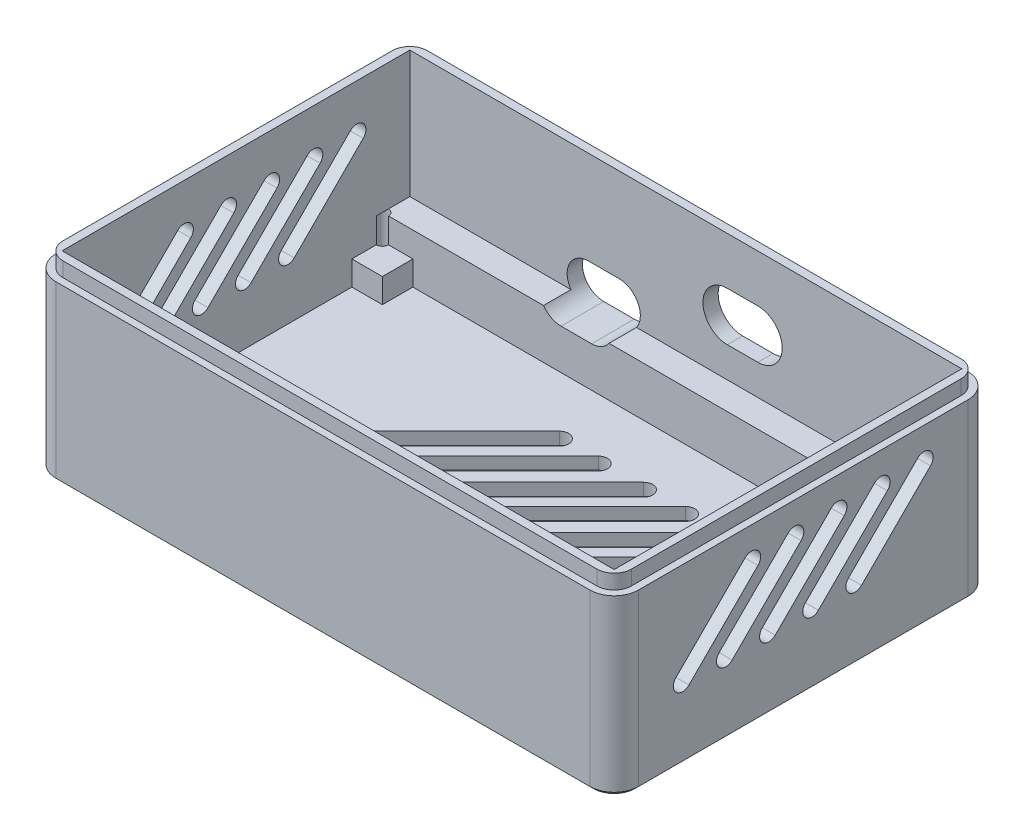
SolidWorks part; units mm, degrees
ref_plane "Front Plane" through (0, 0, 0) normal (0, 0, 1) x (1, 0, 0)
ref_plane "Top Plane" through (0, 0, 0) normal (0, 1, 0) x (1, 0, 0)
ref_plane "Right Plane" through (0, 0, 0) normal (1, 0, 0) x (0, 0, -1)
sketch "Croquis_contorno" plane through (0, 0, 0) normal (0, 1, 0) x (1, 0, 0)
  line L0 (-43.75, -28.75) -> (43.75, -28.75)
  line L1 (47.75, -24.75) -> (47.75, 29.25)
  line L2 (43.75, 33.25) -> (-43.75, 33.25)
  line L3 (-47.75, 29.25) -> (-47.75, -24.75)
  arc A0 (43.75, -28.75) -> (47.75, -24.75) centre (43.75, -24.75) ccw
  arc A1 (47.75, 29.25) -> (43.75, 33.25) centre (43.75, 29.25) ccw
  arc A2 (-43.75, 33.25) -> (-47.75, 29.25) centre (-43.75, 29.25) ccw
  arc A3 (-47.75, -24.75) -> (-43.75, -28.75) centre (-43.75, -24.75) ccw
  dimension "D3" = 4
  dimension "D1" = 95.5
  dimension "D2" = 62
extrude "Cuerpo" add sketch "Croquis_contorno" along normal blind 28.5
ref_plane "Plano_Top Plane_+28_5" through (0, 28.5, 0) normal (0, 1, 0) x (1, 0, 0)
sketch "Croquis_hueco_ESP32" plane through (0, 28.5, 0) normal (0, 1, 0) x (1, 0, 0)
  line L1 (-45.25, -26.25) -> (45.25, -26.25)
  line L2 (-45.25, -26.25) -> (-45.25, 30.75)
  line L3 (-45.25, 30.75) -> (45.25, 30.75)
  line L4 (45.25, -26.25) -> (45.25, 30.75)
  line L5 (-45.25, -26.25) -> (45.25, 30.75) construction
  line L6 (-45.25, 30.75) -> (45.25, -26.25) construction
  dimension "D1" = 90.5
  dimension "D2" = 57
extrude "Hueco_ESP32" cut sketch "Croquis_hueco_ESP32" against normal blind 18.4
ref_plane "Plano_Top Plane_+10_1" through (0, 10.1, 0) normal (0, 1, 0) x (1, 0, 0)
sketch "Croquis_hueco_PCB" plane through (0, 10.1, 0) normal (0, 1, 0) x (1, 0, 0)
  line L0 (45.25, -26.25) -> (45.25, 30.75) construction
  line L1 (-45.25, -26.25) -> (45.25, -26.25)
  line L2 (-45.25, -26.25) -> (-45.25, 26.25)
  line L3 (-45.25, 26.25) -> (45.25, 26.25)
  line L4 (45.25, -26.25) -> (45.25, 26.25)
  line L5 (-45.25, -26.25) -> (45.25, 26.25) construction
  line L6 (-45.25, 26.25) -> (45.25, -26.25) construction
  point P0 (0, 0)
  dimension "D1" = 90.5
  dimension "D2" = 52.5
extrude "Hueco_PCB" cut sketch "Croquis_hueco_PCB" against normal blind 8.1
sketch "Croquis_labio" plane through (0, 28.5, 0) normal (0, 1, 0) x (1, 0, 0)
  line L0 (-43.75, -27.6) -> (43.75, -27.6)
  line L1 (46.6, -24.75) -> (46.6, 29.25)
  line L2 (43.75, 32.1) -> (-43.75, 32.1)
  line L3 (-46.6, 29.25) -> (-46.6, -24.75)
  line L5 (-45.25, -26.25) -> (45.25, -26.25)
  line L6 (-45.25, -26.25) -> (-45.25, 30.75)
  line L7 (-45.25, 30.75) -> (45.25, 30.75)
  line L8 (45.25, -26.25) -> (45.25, 30.75)
  line L9 (-45.25, -26.25) -> (45.25, 30.75) construction
  line L10 (-45.25, 30.75) -> (45.25, -26.25) construction
  arc A0 (43.75, -27.6) -> (46.6, -24.75) centre (43.75, -24.75) ccw
  arc A1 (46.6, 29.25) -> (43.75, 32.1) centre (43.75, 29.25) ccw
  arc A2 (-43.75, 32.1) -> (-46.6, 29.25) centre (-43.75, 29.25) ccw
  arc A3 (-46.6, -24.75) -> (-43.75, -27.6) centre (-43.75, -24.75) ccw
  point P12 (0, 2.25)
  dimension "D3" = 2.85
  dimension "D1" = 93.2
  dimension "D2" = 59.7
extrude "Labio_lip" add sketch "Croquis_labio" along normal blind 2.4
ref_plane "Plano_Top Plane_+2" through (0, 2, 0) normal (0, 1, 0) x (1, 0, 0)
sketch "Croquis_apoyos" plane through (0, 2, 0) normal (0, 1, 0) x (1, 0, 0)
  line L0 (45.25, 26.25) -> (-45.25, 26.25) construction
  line L1 (-45.25, -26.25) -> (-40.25, -26.25)
  line L2 (-45.25, -26.25) -> (-45.25, -21.25)
  line L3 (-45.25, -21.25) -> (-40.25, -21.25)
  line L4 (-40.25, -26.25) -> (-40.25, -21.25)
  line L5 (-45.25, -26.25) -> (-40.25, -21.25) construction
  line L6 (-45.25, -21.25) -> (-40.25, -26.25) construction
  line L7 (-45.25, 21.25) -> (-40.25, 21.25)
  line L8 (-45.25, 21.25) -> (-45.25, 26.25)
  line L9 (-45.25, 26.25) -> (-40.25, 26.25)
  line L10 (-40.25, 21.25) -> (-40.25, 26.25)
  line L11 (-45.25, 21.25) -> (-40.25, 26.25) construction
  line L12 (-45.25, 26.25) -> (-40.25, 21.25) construction
  line L13 (45.25, -26.25) -> (45.25, 26.25) construction
  line L14 (40.25, -26.25) -> (45.25, -26.25)
  line L15 (40.25, -26.25) -> (40.25, -21.25)
  line L16 (40.25, -21.25) -> (45.25, -21.25)
  line L17 (45.25, -26.25) -> (45.25, -21.25)
  line L18 (40.25, -26.25) -> (45.25, -21.25) construction
  line L19 (40.25, -21.25) -> (45.25, -26.25) construction
  line L21 (40.25, 21.25) -> (45.25, 21.25)
  line L22 (40.25, 21.25) -> (40.25, 26.25)
  line L23 (40.25, 26.25) -> (45.25, 26.25)
  line L24 (45.25, 21.25) -> (45.25, 26.25)
  line L25 (40.25, 21.25) -> (45.25, 26.25) construction
  line L26 (40.25, 26.25) -> (45.25, 21.25) construction
  point P0 (-42.75, 23.75)
  point P11 (42.75, -23.75)
  point P18 (42.75, 23.75)
  dimension "D1" = 5
  dimension "D2" = 5
extrude "Apoyos_PCB" add sketch "Croquis_apoyos" along normal blind 4
sketch "Croquis_alivios" plane through (0, 2, 0) normal (0, 1, 0) x (1, 0, 0)
  circle A0 centre (-45.25, -26.25) radius 1
  circle A1 centre (-45.25, 26.25) radius 1
  circle A2 centre (45.25, -26.25) radius 1
  circle A3 centre (45.25, 26.25) radius 1
  dimension "D1" = 2
extrude "Alivios_esquinas" cut sketch "Croquis_alivios" along normal blind 8.1
sketch "Croquis_salidas" plane through (0, 0, 0) normal (0, 0, 1) x (1, 0, 0)
  line L0 (6.8, 19.1) -> (11.8, 19.1) construction
  line L1 (6.8, 23.1) -> (11.8, 23.1)
  line L2 (6.8, 15.1) -> (11.8, 15.1)
  line L3 (-15.96, 12.1) -> (-10.96, 12.1) construction
  line L4 (-15.96, 15.6) -> (-10.96, 15.6)
  line L5 (-15.96, 8.6) -> (-10.96, 8.6)
  arc A0 (6.8, 23.1) -> (6.8, 15.1) centre (6.8, 19.1) ccw
  arc A1 (11.8, 15.1) -> (11.8, 23.1) centre (11.8, 19.1) ccw
  arc A2 (-15.96, 15.6) -> (-15.96, 8.6) centre (-15.96, 12.1) ccw
  arc A3 (-10.96, 8.6) -> (-10.96, 15.6) centre (-10.96, 12.1) ccw
  point P2 (9.3, 19.1)
  point P7 (-13.46, 12.1)
  point P14 (0, 0)
extrude "Salidas_USB_y_panel" cut sketch "Croquis_salidas" against normal through all
sketch "Croquis_ventilas" plane through (0, 0, 0) normal (1, 0, 0) x (0, 0, -1)
  line L0 (-17.549, 11.9431) -> (-6.2353, 23.2569) construction
  line L1 (-18.6097, 13.0038) -> (-7.2959, 24.3175)
  line L2 (-16.4883, 10.8825) -> (-5.1746, 22.1962)
  line L3 (-10.4779, 11.9431) -> (0.8358, 23.2569) construction
  line L4 (-11.5386, 13.0038) -> (-0.2249, 24.3175)
  line L5 (-9.4173, 10.8825) -> (1.8964, 22.1962)
  line L6 (-3.4069, 11.9431) -> (7.9069, 23.2569) construction
  line L7 (-4.4675, 13.0038) -> (6.8462, 24.3175)
  line L8 (-2.3462, 10.8825) -> (8.9675, 22.1962)
  line L9 (3.6642, 11.9431) -> (14.9779, 23.2569) construction
  line L10 (2.6036, 13.0038) -> (13.9173, 24.3175)
  line L11 (4.7249, 10.8825) -> (16.0386, 22.1962)
  line L12 (10.7353, 11.9431) -> (22.049, 23.2569) construction
  line L13 (9.6746, 13.0038) -> (20.9883, 24.3175)
  line L14 (11.7959, 10.8825) -> (23.1097, 22.1962)
  arc A0 (-18.6097, 13.0038) -> (-16.4883, 10.8825) centre (-17.549, 11.9431) ccw
  arc A1 (-5.1746, 22.1962) -> (-7.2959, 24.3175) centre (-6.2353, 23.2569) ccw
  arc A2 (-11.5386, 13.0038) -> (-9.4173, 10.8825) centre (-10.4779, 11.9431) ccw
  arc A3 (1.8964, 22.1962) -> (-0.2249, 24.3175) centre (0.8358, 23.2569) ccw
  arc A4 (-4.4675, 13.0038) -> (-2.3462, 10.8825) centre (-3.4069, 11.9431) ccw
  arc A5 (8.9675, 22.1962) -> (6.8462, 24.3175) centre (7.9069, 23.2569) ccw
  arc A6 (2.6036, 13.0038) -> (4.7249, 10.8825) centre (3.6642, 11.9431) ccw
  arc A7 (16.0386, 22.1962) -> (13.9173, 24.3175) centre (14.9779, 23.2569) ccw
  arc A8 (9.6746, 13.0038) -> (11.7959, 10.8825) centre (10.7353, 11.9431) ccw
  arc A9 (23.1097, 22.1962) -> (20.9883, 24.3175) centre (22.049, 23.2569) ccw
  point P2 (-11.8921, 17.6)
  point P7 (-4.8211, 17.6)
  point P14 (2.25, 17.6)
  point P21 (9.3211, 17.6)
  point P28 (16.3921, 17.6)
  point P35 (0, 0)
extrude "Ventilas_laterales" cut sketch "Croquis_ventilas" along normal through all and the other way through all
sketch "Croquis_rejilla_piso" plane through (0, 0, 0) normal (0, 1, 0) x (1, 0, 0)
  line L0 (-35.7089, -12.2457) -> (-6.7175, 16.7457) construction
  line L1 (-36.7696, -11.185) -> (-7.7782, 17.8063)
  line L2 (-34.6482, -13.3063) -> (-5.6569, 15.685)
  line L3 (-28.6378, -12.2457) -> (0, 16.3921) construction
  line L4 (-29.6985, -11.185) -> (-1.0607, 17.4528)
  line L5 (-27.5772, -13.3063) -> (1.0607, 15.3315)
  line L6 (-21.2132, -12.2457) -> (7.4246, 16.3921) construction
  line L7 (-22.2739, -11.185) -> (6.364, 17.4528)
  line L8 (-20.1525, -13.3063) -> (8.4853, 15.3315)
  line L9 (-14.3189, -12.2457) -> (14.3189, 16.3921) construction
  line L10 (-15.3796, -11.185) -> (13.2583, 17.4528)
  line L11 (-13.2583, -13.3063) -> (15.3796, 15.3315)
  line L12 (-6.8943, -12.2457) -> (21.7435, 16.3921) construction
  line L13 (-7.955, -11.185) -> (20.6829, 17.4528)
  line L14 (-5.8336, -13.3063) -> (22.8042, 15.3315)
  line L15 (0, -12.2457) -> (28.6378, 16.3921) construction
  line L16 (-1.0607, -11.185) -> (27.5772, 17.4528)
  line L17 (1.0607, -13.3063) -> (29.6985, 15.3315)
  line L18 (6.364, -12.2457) -> (35.5321, 16.9225) construction
  line L19 (5.3033, -11.185) -> (34.4715, 17.9831)
  line L20 (7.4246, -13.3063) -> (36.5928, 15.8618)
  arc A0 (-36.7696, -11.185) -> (-34.6482, -13.3063) centre (-35.7089, -12.2457) ccw
  arc A1 (-5.6569, 15.685) -> (-7.7782, 17.8063) centre (-6.7175, 16.7457) ccw
  arc A2 (-29.6985, -11.185) -> (-27.5772, -13.3063) centre (-28.6378, -12.2457) ccw
  arc A3 (1.0607, 15.3315) -> (-1.0607, 17.4528) centre (0, 16.3921) ccw
  arc A4 (-22.2739, -11.185) -> (-20.1525, -13.3063) centre (-21.2132, -12.2457) ccw
  arc A5 (8.4853, 15.3315) -> (6.364, 17.4528) centre (7.4246, 16.3921) ccw
  arc A6 (-15.3796, -11.185) -> (-13.2583, -13.3063) centre (-14.3189, -12.2457) ccw
  arc A7 (15.3796, 15.3315) -> (13.2583, 17.4528) centre (14.3189, 16.3921) ccw
  arc A8 (-7.955, -11.185) -> (-5.8336, -13.3063) centre (-6.8943, -12.2457) ccw
  arc A9 (22.8042, 15.3315) -> (20.6829, 17.4528) centre (21.7435, 16.3921) ccw
  arc A10 (-1.0607, -11.185) -> (1.0607, -13.3063) centre (0, -12.2457) ccw
  arc A11 (29.6985, 15.3315) -> (27.5772, 17.4528) centre (28.6378, 16.3921) ccw
  arc A12 (5.3033, -11.185) -> (7.4246, -13.3063) centre (6.364, -12.2457) ccw
  arc A13 (36.5928, 15.8618) -> (34.4715, 17.9831) centre (35.5321, 16.9225) ccw
  point P2 (-21.2132, 2.25)
  point P7 (-14.3189, 2.0732)
  point P14 (-6.8943, 2.0732)
  point P21 (0, 2.0732)
  point P28 (7.4246, 2.0732)
  point P35 (14.3189, 2.0732)
  point P42 (20.948, 2.3384)
  point P49 (0, 0)
extrude "Rejilla_piso" cut sketch "Croquis_rejilla_piso" along normal blind 2
chamfer "Chaflan_base" distance 0.6 angle 45 8 edges at (0, 0, 28.75) (46.5784, 0, 27.5784) (47.75, 0, -2.25) (46.5784, 0, -32.0784) (0, 0, -33.25) (-46.5784, 0, -32.0784) (-47.75, 0, -2.25) (-46.5784, 0, 27.5784)
